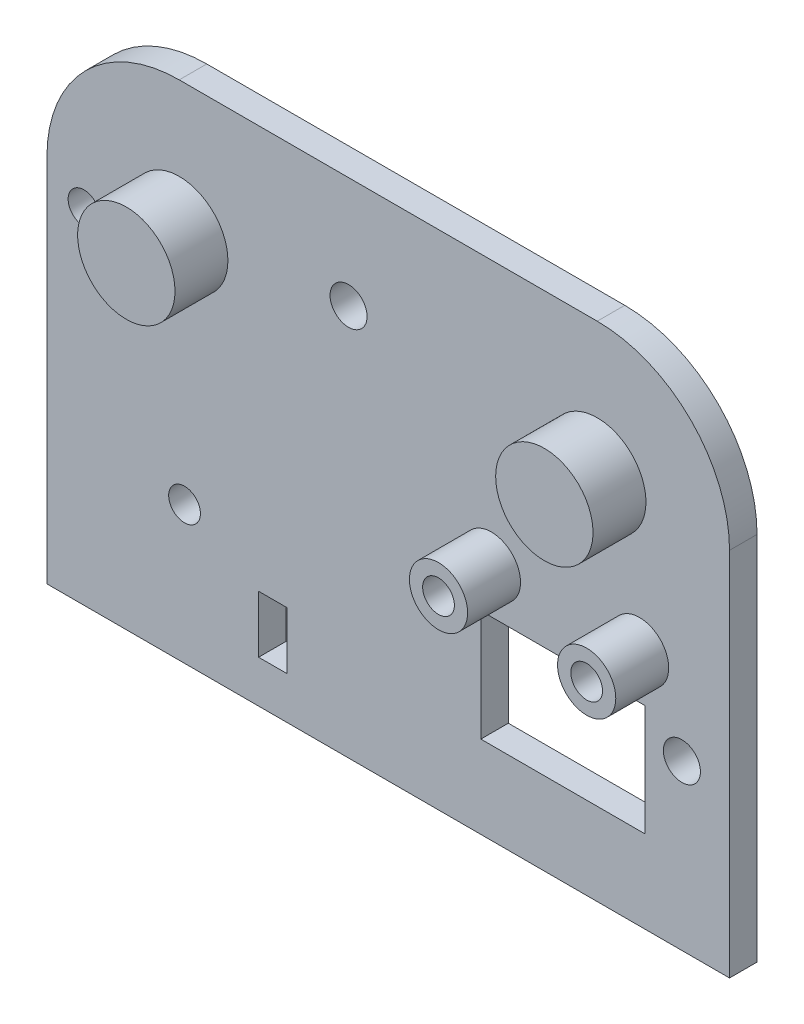
SolidWorks part; units mm, degrees
ref_plane "前视基准面" through (0, 0, 0) normal (0, 0, 1) x (1, 0, 0)
ref_plane "上视基准面" through (0, 0, 0) normal (0, 1, 0) x (1, 0, 0)
ref_plane "右视基准面" through (0, 0, 0) normal (1, 0, 0) x (0, 0, -1)
other "Configuration Table"
sketch "草图1" plane through (0, 0, 0) normal (0, 0, 1) x (1, 0, 0)
  line L1 (-32.25, 23.75) -> (32.25, 23.75)
  line L2 (-32.25, 23.75) -> (-32.25, -23.75)
  line L3 (-32.25, -23.75) -> (32.25, -23.75)
  line L4 (32.25, 23.75) -> (32.25, -23.75)
  dimension "D1" = 64.5
  dimension "D2" = 47.5
  dimension "D3" = 23.75
  dimension "D4" = 32.25
extrude "凸台-拉伸1" add sketch "草图1" along normal blind 2.6
fillet "圆角1" radius 12.5 2 edges at (32.25, 23.75, 1.3) (-32.25, 23.75, 1.3)
sketch "草图2" plane through (0, 0, 2.6) normal (0, 0, 1) x (1, 0, 0)
  line L0 (-32.25, -23.75) -> (32.25, -23.75) construction
  line L1 (-32.25, 11.25) -> (-32.25, -23.75) construction
  line L2 (19.75, 23.75) -> (-19.75, 23.75) construction
  line L3 (32.25, -23.75) -> (32.25, 11.25) construction
  line L4 (-12.25, -14.35) -> (-9.55, -14.35)
  line L5 (-12.25, -14.35) -> (-12.25, -19.75)
  line L6 (-12.25, -19.75) -> (-9.55, -19.75)
  line L7 (-9.55, -14.35) -> (-9.55, -19.75)
  line L8 (8.75, -5.45) -> (24.25, -5.45)
  line L9 (8.75, -5.45) -> (8.75, -15.95)
  line L10 (8.75, -15.95) -> (24.25, -15.95)
  line L11 (24.25, -5.45) -> (24.25, -15.95)
  circle A0 centre (-19.25, -10.75) radius 1.5
  circle A1 centre (-28.75, 8.75) radius 1.5
  circle A3 centre (27.75, -8.25) radius 1.75
  circle A4 centre (23.75, -1.25) radius 1.5
  circle A5 centre (9.75, -1.25) radius 1.5
  circle A6 centre (-3.75, 13.25) radius 1.75
  dimension "D3" = 3
  dimension "D4" = 3.5
  dimension "D6" = 3
  dimension "D16" = 3.5
  dimension "D19" = 3
  dimension "D20" = 3
  dimension "D24" = 36
  dimension "D26" = 3.5
  dimension "D1" = 13
  dimension "D2" = 13
  dimension "D5" = 15
  dimension "D7" = 2.7
  dimension "D8" = 4
  dimension "D9" = 20
  dimension "D10" = 5.4
  dimension "D11" = 8
  dimension "D12" = 15.5
  dimension "D13" = 10.5
  dimension "D14" = 7.8
  dimension "D15" = 15.5
  dimension "D17" = 4.5
  dimension "D18" = 8.5
  dimension "D21" = 14
  dimension "D22" = 22.5
  dimension "D23" = 22.5
  dimension "D25" = 10.5
extrude "切除-拉伸1" cut sketch "草图2" against normal blind 2.6
sketch "草图3" plane through (0, 0, 2.6) normal (0, 0, 1) x (1, 0, 0)
  line L0 (0, 24.937) -> (0, -5.011) construction
  circle A0 centre (-19.75, 11.25) radius 4.6
  circle A1 centre (19.75, 11.25) radius 4.6
  circle A2 centre (9.75, -1.25) radius 2.75
  circle A3 centre (23.75, -1.25) radius 2.75
  dimension "D1" = 5.5
  dimension "D2" = 5.5
extrude "凸台-拉伸2" add sketch "草图3" along normal blind 5
sketch "草图4" plane through (0, 0, 0) normal (0, 0, -1) x (-1, 0, 0)
  circle A0 centre (-23.75, -1.25) radius 1.5
  circle A1 centre (-9.75, -1.25) radius 1.5
extrude "切除-拉伸2" cut sketch "草图4" against normal blind 26
